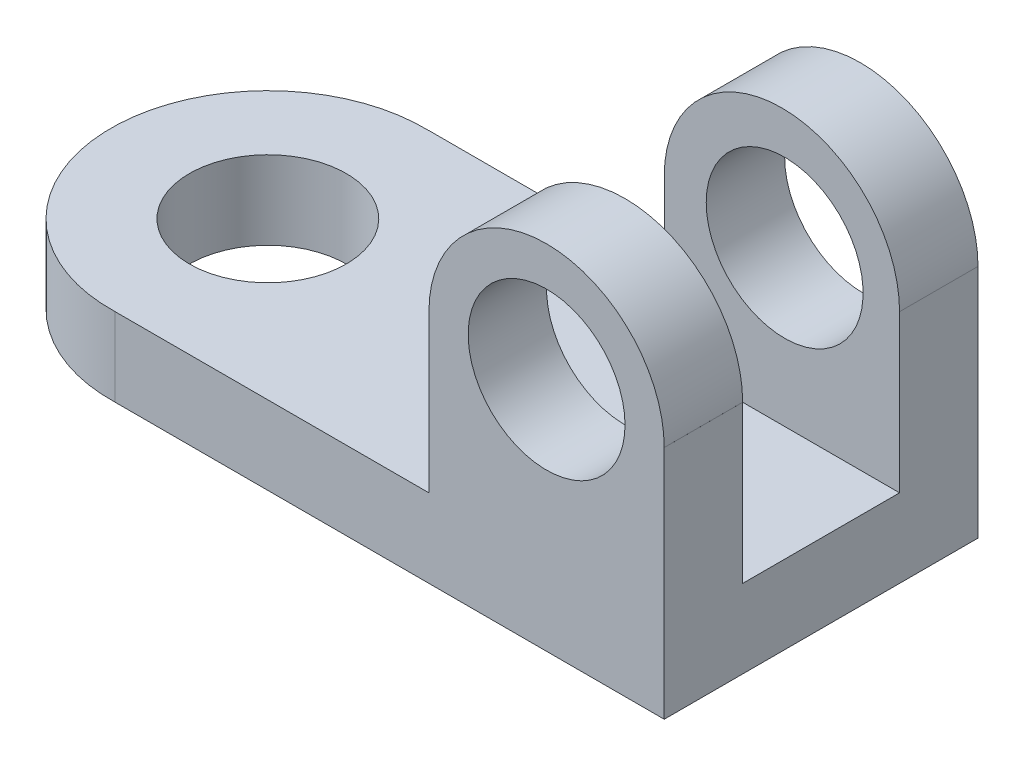
SolidWorks part; units mm, degrees
material "Brass"
ref_plane "Front Plane" through (0, 0, 0) normal (0, 0, 1) x (1, 0, 0)
ref_plane "Top Plane" through (0, 0, 0) normal (0, 1, 0) x (1, 0, 0)
ref_plane "Right Plane" through (0, 0, 0) normal (1, 0, 0) x (0, 0, -1)
sketch "Croquis1" plane through (0, 0, 0) normal (0, 1, 0) x (1, 0, 0)
  line L0 (0, 0) -> (0, 50.8)
  line L1 (0, 50.8) -> (-88.9, 50.8)
  line L2 (0, 0) -> (-88.9, 0)
  line L3 (-88.9, 50.8) -> (-88.9, 50.7824)
  arc A0 (-88.9, 50.7824) -> (-88.9, 0) centre (-89.5689, 25.3912) ccw
  dimension "D2" = 50.8
  dimension "D3" = 88.9
  dimension "D1" = 50.8
  dimension "D4" = 88.9
extrude "Saliente-Extruir2" add sketch "Croquis1" along normal blind 12.7
sketch "Croquis5" plane through (0, 0, 0) normal (0, 0, 1) x (1, 0, 0)
  line L0 (0, 12.7) -> (0, 38.1)
  line L1 (-38.1, 12.7) -> (-38.1, 38.1)
  line L2 (-88.9, 12.7) -> (0, 12.7) construction
  line L3 (-38.1, 38.1) -> (-38.0974, 38.1)
  line L4 (-38.1, 12.7) -> (0, 12.7)
  line L5 (-0.0026, 38.1) -> (0, 38.1)
  arc A0 (-0.0026, 38.1) -> (-38.0974, 38.1) centre (-19.05, 38.1) ccw
  point P8 (-19.05, 38.1)
  dimension "D1" = 38.1
  dimension "D2" = 25.4
extrude "Saliente-Extruir4" add sketch "Croquis5" against normal blind 12.7
sketch "Croquis7" plane through (0, 0, 0) normal (0, 0, 1) x (1, 0, 0)
  circle A0 centre (-19.05, 38.1) radius 12.7
  dimension "D1" = 25.4
extrude "Cortar-Extruir1" cut sketch "Croquis7" against normal blind 12.7
sketch "Croquis8" plane through (0, 0, -50.8) normal (0, 0, -1) x (-1, 0, 0)
  line L0 (38.1, 12.7) -> (38.0974, 38.1)
  line L2 (0, 38.1) -> (0, 12.7)
  line L3 (0, 12.7) -> (38.1, 12.7)
  arc A0 (38.0974, 38.1) -> (0, 38.1) centre (19.0487, 38.1) ccw
extrude "Saliente-Extruir5" add sketch "Croquis8" against normal blind 12.7
sketch "Croquis9" plane through (0, 0, -50.8) normal (0, 0, -1) x (-1, 0, 0)
  circle A0 centre (18.604, 37.7608) radius 12.7
  dimension "D1" = 25.4
extrude "Cortar-Extruir2" cut sketch "Croquis9" against normal blind 28.702
sketch "Croquis10" plane through (0, 12.7, 0) normal (0, 1, 0) x (1, 0, 0)
  line L0 (-89.5689, 50.7912) -> (-89.5689, -0.0088) construction
  arc A0 (-88.9, 50.7824) -> (-88.9, 0) centre (-89.5689, 25.3912) ccw construction
  circle A1 centre (-89.5689, 25.3912) radius 12.7
  point P8 (0, 0)
  dimension "D1" = 25.4
extrude "Cortar-Extruir3" cut sketch "Croquis10" against normal blind 32.004
